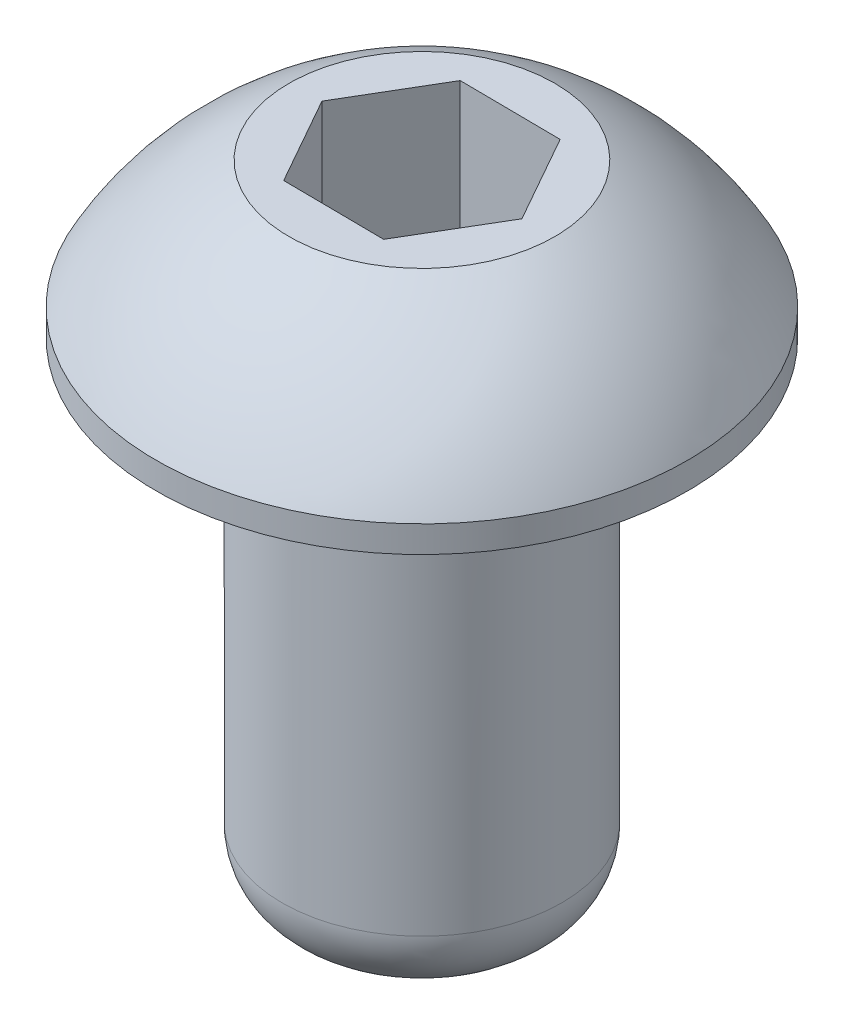
SolidWorks part; units mm, degrees
ref_plane "Front Plane" through (0, 0, 0) normal (0, 0, 1) x (1, 0, 0)
ref_plane "Top Plane" through (0, 0, 0) normal (0, 1, 0) x (1, 0, 0)
ref_plane "Right Plane" through (0, 0, 0) normal (1, 0, 0) x (0, 0, -1)
sketch "Sketch1" plane through (0, 0, 0) normal (0, 1, 0) x (1, 0, 0)
  circle A0 centre (0, 0) radius 2
  dimension "D1" = 4
extrude "Boss-Extrude1" add sketch "Sketch1" along normal blind 7
sketch "Sketch2" plane through (0, 0, 0) normal (0, 0, 1) x (1, 0, 0)
  line L0 (0, 7) -> (3.8, 7)
  line L2 (2, 7) -> (-2, 7) construction
  line L3 (3.8, 7) -> (3.8, 7.38)
  line L4 (0, 7) -> (0, 9.2)
  line L5 (0, 9.2) -> (1.9, 9.2)
  arc A0 (3.8, 7.38) -> (1.9, 9.2) centre (0.0036, 5.3185) ccw
  point P7 (0.8103, 28.843)
  dimension "D3" = 4.32
  dimension "D1" = 3.8
  dimension "D2" = 0.38
  dimension "D4" = 1.9
  dimension "D5" = 2.2
revolve "Revolve1" add sketch "Sketch2" angle 360 about L4
sketch "Sketch3" plane through (0, 9.2, 0) normal (0, 1, 0) x (1, 0, 0)
  line L1 (-0.7336, -1.243) -> (0.7097, -1.2568)
  line L2 (0.7097, -1.2568) -> (1.4433, -0.0138)
  line L3 (1.4433, -0.0138) -> (0.7336, 1.243)
  line L4 (0.7336, 1.243) -> (-0.7097, 1.2568)
  line L5 (-0.7097, 1.2568) -> (-1.4433, 0.0138)
  line L6 (-1.4433, 0.0138) -> (-0.7336, -1.243)
  circle A0 centre (0, 0) radius 1.25 construction
  dimension "D1" = 2.5
extrude "Cut-Extrude1" cut sketch "Sketch3" against normal blind 2
fillet "Fillet1" radius 1 2 edges at (0, 7, 2) (0, 0, 2)
